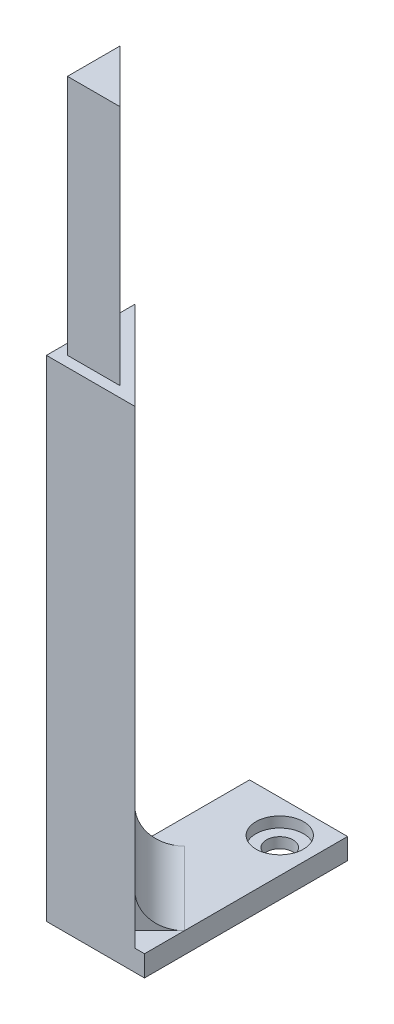
SolidWorks part; units mm, degrees
ref_plane "Front Plane" through (0, 0, 0) normal (0, 0, 1) x (1, 0, 0)
ref_plane "Top Plane" through (0, 0, 0) normal (0, 1, 0) x (1, 0, 0)
ref_plane "Right Plane" through (0, 0, 0) normal (1, 0, 0) x (0, 0, -1)
sketch "Sketch1" plane through (0, 0, 0) normal (0, 1, 0) x (1, 0, 0)
  line L9 (0, 0) -> (0, 15)
  line L35 (0, 0) -> (15, 0)
  line L50 (0, 15) -> (15, 0)
  point P0 (0, 0)
  point P5 (0, 0)
  point P6 (0, 0)
  point P9 (0, 0)
  point P10 (0, 0)
  dimension "D1" = 15
  dimension "D2" = 15
extrude "Boss-Extrude3" add sketch "Sketch1" along normal blind 320
sketch "Sketch7" plane through (0, 0, 0) normal (0, 0, 1) x (1, 0, 0)
  line L0 (0, 209) -> (0, 320)
  line L1 (0, 320) -> (0, 0) construction
  line L2 (0, 320) -> (15, 320)
  line L3 (0, 0) -> (15, 0) construction
  line L4 (15, 320) -> (15, 209)
  line L5 (15, 320) -> (15, 0) construction
  line L6 (15, 209) -> (0, 209)
  dimension "D1" = 209
extrude "Cut-Extrude3" cut sketch "Sketch7" against normal through all
sketch "Sketch8" plane through (0, 0, 0) normal (0, -1, 0) x (1, 0, 0)
  line L3 (-3, -22.2426) -> (-3, 3)
  line L4 (-3, 3) -> (22.2426, 3)
  line L5 (22.2426, 3) -> (-3, -22.2426)
extrude "Boss-Extrude5" add sketch "Sketch8" against normal blind 140
sketch "Sketch4" plane through (0, 0, 0) normal (0, -1, 0) x (1, 0, 0)
  line L7 (25, -55) -> (0, -55)
  line L9 (25, 3) -> (-3, 3)
  line L10 (-3, 3) -> (-3, -55)
  line L11 (-3, -55) -> (0, -55)
  line L12 (25, 3) -> (25, -55)
  circle A0 centre (15.04, -45.59) radius 3.8
  dimension "D3" = 7.6
  dimension "D5" = 48.59
  dimension "D4" = 9.96
  dimension "D1" = 28
  dimension "D2" = 58
extrude "Boss-Extrude4" add sketch "Sketch4" against normal blind 6
sketch "Sketch9" plane through (0, 6, 0) normal (0, 1, 0) x (1, 0, 0)
  line L0 (-3, 22.2426) -> (4.0711, 29.3137)
  line L1 (4.0711, 29.3137) -> (25, 8.3848)
  line L2 (25, -3) -> (25, 55) construction
  line L3 (25, 8.3848) -> (17.9289, 1.3137)
  line L4 (-3, 22.2426) -> (22.2426, -3) construction
  line L5 (17.9289, 1.3137) -> (-3, 22.2426)
  dimension "D1" = 10
extrude "Boss-Extrude6" add sketch "Sketch9" along normal blind 10
sketch "Sketch10" plane through (8.3076, 0, 8.3076) normal (0.7071, 0, 0.7071) x (0.7071, 0, -0.7071)
  line L0 (13.6066, 16) -> (23.6066, 16)
  line L1 (23.6066, 16) -> (23.6066, 6)
  arc A0 (13.6066, 16) -> (23.6066, 6) centre (23.6066, 16) ccw
extrude "Cut-Extrude4" cut sketch "Sketch10" against normal through all
sketch "Sketch11" plane through (0, 6, 0) normal (0, 1, 0) x (1, 0, 0)
  circle A0 centre (15.04, 45.59) radius 6.8
  circle A1 centre (15.04, 45.59) radius 3.8 construction
  dimension "D1" = 3
extrude "Cut-Extrude5" cut sketch "Sketch11" against normal blind 3
